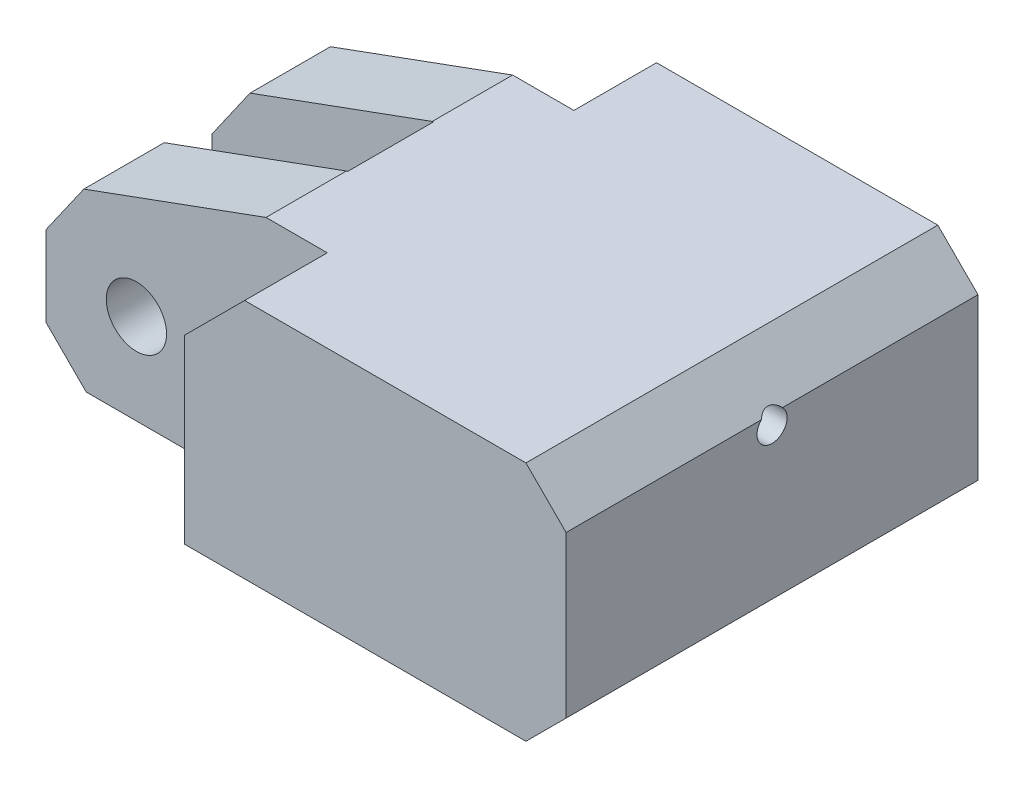
SolidWorks part; units mm, degrees
ref_plane "Спереди" through (0, 0, 0) normal (0, 0, 1) x (1, 0, 0)
ref_plane "Сверху" through (0, 0, 0) normal (0, 1, 0) x (1, 0, 0)
ref_plane "Справа" through (0, 0, 0) normal (1, 0, 0) x (0, 0, -1)
sketch "Эскиз2" plane through (0, 0, 0) normal (1, 0, 0) x (0, 0, -1)
  line L1 (-10.25, 6) -> (10.25, 6)
  line L2 (-10.25, 6) -> (-10.25, -6)
  line L3 (-10.25, -6) -> (10.25, -6)
  line L4 (10.25, 6) -> (10.25, -6)
  line L5 (-10.25, 6) -> (10.25, -6) construction
  line L6 (-10.25, -6) -> (10.25, 6) construction
  point P0 (0, 0)
extrude "Вытянуть1" add sketch "Эскиз2" along normal blind 30
sketch "Эскиз3" plane through (0, 6, 0) normal (0, 1, 0) x (1, 0, 0)
  line L0 (0, 0) -> (-9.2006, 0) construction
  line L1 (0, 10.25) -> (0, -10.25) construction
  line L2 (-11, 2.1371) -> (11, 2.1371)
  line L3 (-11, 2.1371) -> (-11, -2.1371)
  line L4 (-11, -2.1371) -> (11, -2.1371)
  line L5 (11, 2.1371) -> (11, -2.1371)
  line L6 (-11, 2.1371) -> (11, -2.1371) construction
  line L7 (-11, -2.1371) -> (11, 2.1371) construction
  point P1 (0, 0)
  dimension "D1" = 11
extrude "Вырез-Вытянуть1" cut sketch "Эскиз3" against normal through all
sketch "Эскиз10" plane through (0, 6, 0) normal (0, 1, 0) x (1, 0, 0)
  line L0 (5.6157, 0) -> (-3.5713, 0) construction
  line L1 (0, 10.25) -> (0, 2.1371) construction
  line L2 (11, 2.1371) -> (0, 2.1371) construction
  line L3 (-6.1065, 15.2007) -> (11, 15.2007)
  line L4 (-6.1065, 15.2007) -> (-6.1065, 6.1371)
  line L5 (-6.1065, 6.1371) -> (11, 6.1371)
  line L6 (11, 15.2007) -> (11, 6.1371)
  line L7 (-6.1065, -15.2007) -> (11, -15.2007)
  line L8 (-6.1065, -15.2007) -> (-6.1065, -6.1371)
  line L9 (-6.1065, -6.1371) -> (11, -6.1371)
  line L10 (11, -15.2007) -> (11, -6.1371)
  dimension "D1" = 4
  dimension "D2" = 11
extrude "Вырез-Вытянуть3" cut sketch "Эскиз10" against normal through all
sketch "Эскиз11" plane through (0, 0, 6.1371) normal (0, 0, 1) x (1, 0, 0)
  line L0 (0, -6) -> (0, 6) construction
  line L2 (11, -6) -> (0, -6) construction
  circle A0 centre (4.5, -1.5) radius 1.5
  dimension "D1" = 4.5
  dimension "D2" = 4.5
extrude "Вытянуть6" cut sketch "Эскиз11" against normal through all
sketch "Эскиз12" plane through (11, 0, 0) normal (-1, 0, 0) x (0, 0, 1)
  circle A0 centre (-1.7914, -3.4073) radius 0.75
extrude "Вырез-Вытянуть4" cut sketch "Эскиз12" against normal blind 12
sketch "Эскиз13" plane through (0, 0, 10.25) normal (0, 0, 1) x (1, 0, 0)
  line L0 (10.95, 6) -> (0, 6)
  line L1 (30, 6) -> (11, 6) construction
  line L2 (0, -6) -> (0, 6) construction
  line L3 (0, 6) -> (0, 2)
  line L4 (0, 2) -> (10.95, 6)
  line L6 (40.0058, 6) -> (40.0058, 2)
  line L7 (11, 6) -> (0, 6) construction
  line L8 (40.0058, 2) -> (30.0058, 6)
  line L9 (30.0058, 6) -> (40.0058, 6)
  dimension "D2" = 4
  dimension "D1" = 10.95
  dimension "D3" = 10
extrude "Вытянуть7" cut sketch "Эскиз13" against normal through all
chamfer "Фаска5" distance 2 angle 45 4 edges at (0, -6, 4.1371) (0, -6, -4.1371) (30, -6, 0) (30, 6, 0)
chamfer "Фаска6" distance 2 angle 35 2 edges at (0, 2, 4.1371) (0, 2, -4.1371)
sketch "Эскиз14" plane through (11, 0, 0) normal (-1, 0, 0) x (0, 0, 1)
  circle A0 centre (0, 3.4654) radius 0.75
extrude "Вырез-Вытянуть5" cut sketch "Эскиз14" against normal through all
chamfer "Фаска8" distance 3 angle 45 2 edges at (11, 6, 8.1936) (11, 6, -8.1936)
sketch "Эскиз15" plane through (0, -6, 0) normal (0, -1, 0) x (1, 0, 0)
  line L0 (11, 10.25) -> (11, 6.1371) construction
  line L1 (16, 6.25) -> (25, 6.25)
  line L2 (14, 4.25) -> (14, -4.25)
  line L3 (16, -6.25) -> (25, -6.25)
  line L4 (27, 4.25) -> (27, -4.25)
  line L5 (28, 10.25) -> (11, 10.25) construction
  line L6 (28, -10.25) -> (11, -10.25) construction
  line L7 (30, 10.25) -> (30, -10.25) construction
  arc A0 (16, 6.25) -> (14, 4.25) centre (16, 4.25) ccw
  arc A1 (27, 4.25) -> (25, 6.25) centre (25, 4.25) ccw
  arc A2 (25, -6.25) -> (27, -4.25) centre (25, -4.25) ccw
  arc A3 (16, -6.25) -> (14, -4.25) centre (16, -4.25) cw
  dimension "D5" = 2
  dimension "D1" = 3
  dimension "D2" = 4
  dimension "D3" = 4
  dimension "D4" = 3
extrude "Вытянуть8" cut sketch "Эскиз15" against normal blind 10
